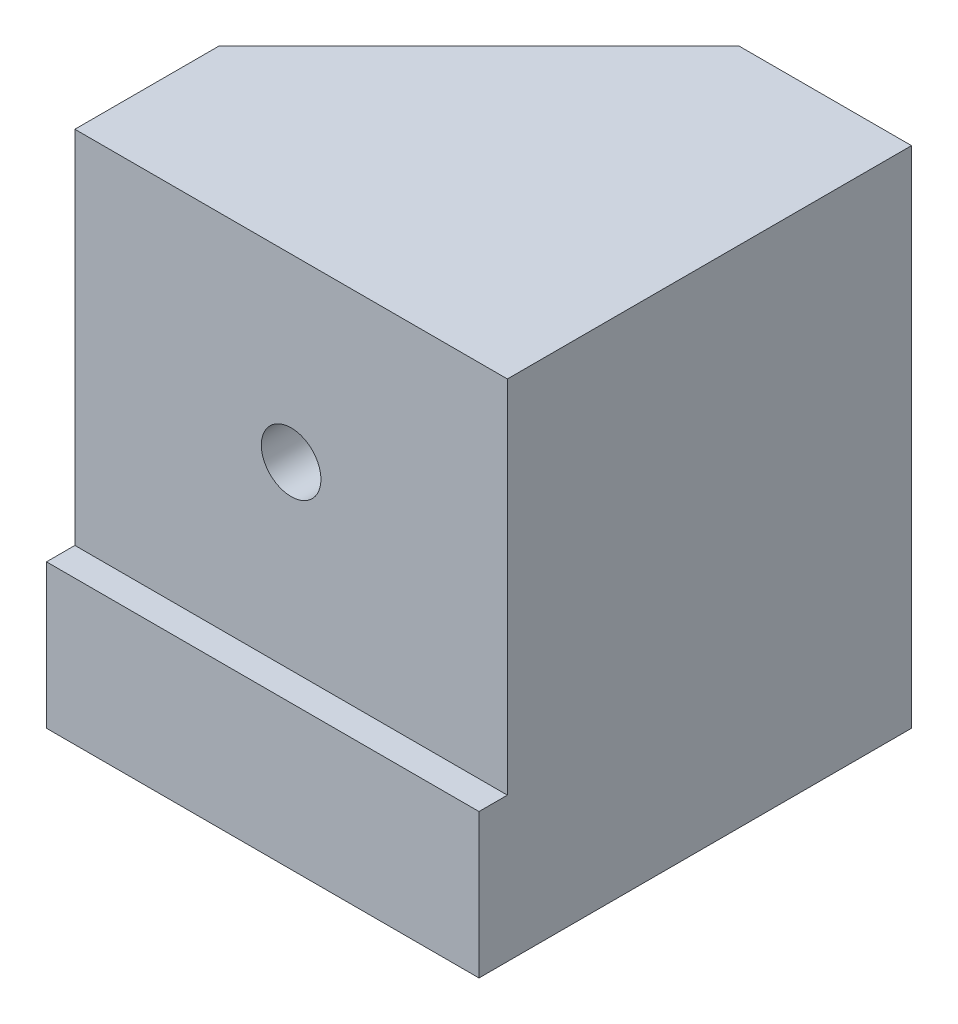
SolidWorks part; units mm, degrees
ref_plane "Front Plane" through (0, 0, 0) normal (0, 0, 1) x (1, 0, 0)
ref_plane "Top Plane" through (0, 0, 0) normal (0, 1, 0) x (1, 0, 0)
ref_plane "Right Plane" through (0, 0, 0) normal (1, 0, 0) x (0, 0, -1)
sketch "Sketch1" plane through (0, 0, 0) normal (0, 1, 0) x (1, 0, 0)
  line L1 (0, 0) -> (76.2, 0)
  line L2 (0, 0) -> (0, 76.2)
  line L3 (0, 76.2) -> (76.2, 76.2)
  line L4 (76.2, 0) -> (76.2, 76.2)
  dimension "D1" = 76.2
  dimension "D2" = 76.2
extrude "Boss-Extrude1" add sketch "Sketch1" along normal blind 88.9
sketch "Sketch2" plane through (0, 0, 0) normal (0, 0, 1) x (1, 0, 0)
  line L1 (0, 0) -> (38.1, 0)
  line L2 (0, 0) -> (0, 57.15)
  line L3 (0, 57.15) -> (38.1, 57.15)
  line L4 (38.1, 0) -> (38.1, 57.15)
  circle A0 centre (38.1, 57.15) radius 5.25
  dimension "D1" = 38.1
  dimension "D2" = 57.15
extrude "Cut-Extrude1" cut sketch "Sketch2" against normal blind 300 contours A0
sketch "Sketch3" plane through (0, 0, 0) normal (0, 0, 1) x (1, 0, 0)
  line L0 (76.2, 88.9) -> (76.2, 0) construction
  line L1 (0, 88.9) -> (76.2, 88.9)
  line L2 (0, 88.9) -> (0, 25.4)
  line L3 (0, 25.4) -> (76.2, 25.4)
  line L4 (76.2, 88.9) -> (76.2, 25.4)
  dimension "D1" = 63.5
extrude "Cut-Extrude2" cut sketch "Sketch3" against normal blind 5
sketch "Sketch5" plane through (0, 88.9, 0) normal (0, 1, 0) x (1, 0, 0)
  line L0 (0, 5) -> (0, 30.4)
  line L1 (0, 76.2) -> (0, 5) construction
  line L2 (0, 30.4) -> (45.8, 76.2)
  line L3 (76.2, 76.2) -> (0, 76.2) construction
  line L4 (45.8, 76.2) -> (76.2, 76.2)
  line L5 (45.8, 76.2) -> (0, 76.2)
  line L6 (0, 76.2) -> (0, 30.4)
  line M3 (76.2, 76.2) -> (0, 76.2)
  line M4 (0, 76.2) -> (0, 5)
  dimension "D1" = 30.4
  dimension "D2" = 25.4
extrude "Cut-Extrude5" cut sketch "Sketch5" against normal through all contours L2 M4 M3
